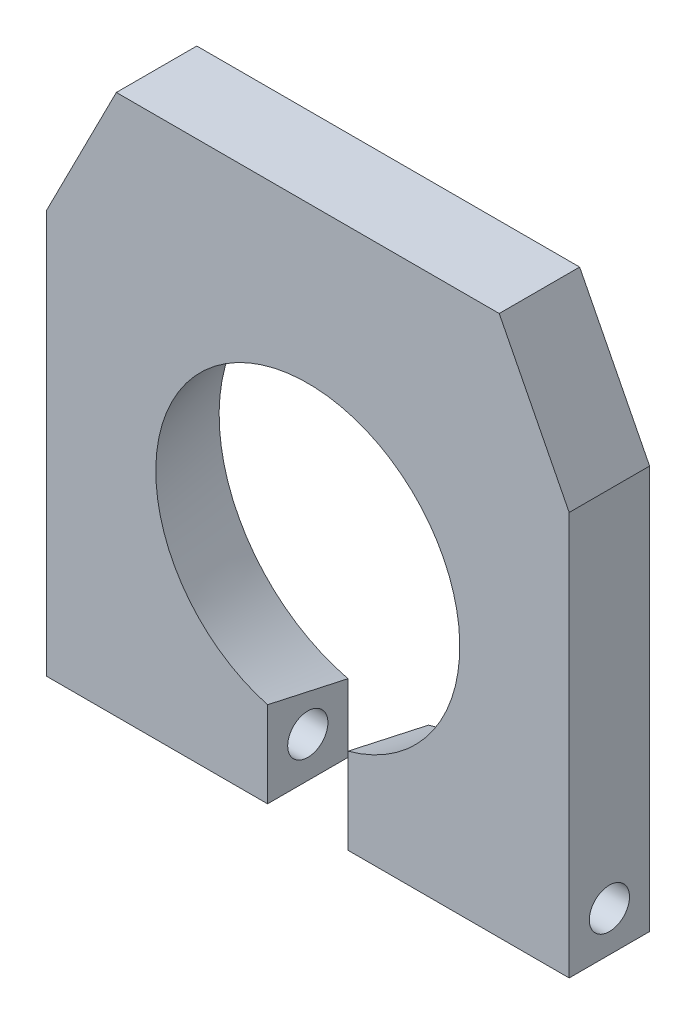
SolidWorks part; units mm, degrees
material "Alliage 1060"
ref_plane "Plan de face" through (0, 0, 0) normal (0, 0, 1) x (1, 0, 0)
ref_plane "Plan de dessus" through (0, 0, 0) normal (0, 1, 0) x (1, 0, 0)
ref_plane "Plan de droite" through (0, 0, 0) normal (1, 0, 0) x (0, 0, -1)
sketch "Esquisse1" plane through (0, 0, 0) normal (0, 0, 1) x (1, 0, 0)
  line L0 (34.925, -85.344) -> (34.925, -71.7887)
  line L1 (0, 0) -> (82.55, 0)
  line L2 (0, 0) -> (0, -85.344)
  line L3 (0, -85.344) -> (34.925, -85.344)
  line L4 (82.55, 0) -> (82.55, -85.344)
  line L5 (47.625, -85.344) -> (82.55, -85.344)
  line L6 (47.625, -71.7887) -> (47.625, -85.344)
  line L7 (34.925, -85.344) -> (47.625, -85.344) construction
  arc A0 (47.625, -71.7887) -> (34.925, -71.7887) centre (41.275, -48.644) ccw
  point P6 (41.275, -85.344)
  point P7 (41.275, 0)
  dimension "D3" = 48
  dimension "D1" = 82.55
  dimension "D2" = 85.344
  dimension "D4" = 12.7
  dimension "D5" = 12.7
extrude "Boss.-Extru.1" add sketch "Esquisse1" along normal blind 12.7
ref_axis "Axe1" through (41.275, -48.644, 0) along (0, 0, 1)
sketch "Esquisse2" plane through (82.55, 0, 0) normal (1, 0, 0) x (0, 0, -1)
  line L0 (-6.35, -78.994) -> (-12.7, -85.344) construction
  line L1 (-6.35, -78.994) -> (0, -85.344) construction
  line L2 (-6.35, -78.994) -> (-12.7, -78.994) construction
  line L3 (-12.7, -85.344) -> (-12.7, 0) construction
  line L4 (-6.35, -78.994) -> (-6.35, -85.344) construction
  line L5 (-12.7, -85.344) -> (0, -85.344) construction
  circle A0 centre (-6.35, -78.994) radius 3.175
  dimension "D1" = 6.35
extrude "Enlèv. mat.-Extru.1" cut sketch "Esquisse2" against normal through all
ref_plane "Plan1" through (0, -48.644, 0) normal (0, -1, 0) x (1, 0, 0)
sketch "Esquisse4" plane through (0, -48.644, 0) normal (0, -1, 0) x (1, 0, 0)
  line L0 (17.275, 12.7) -> (14.5338, -0.1963)
  line L1 (17.275, 12.7) -> (34.925, 12.7)
  line L2 (14.5338, -0.1963) -> (34.925, -0.1963)
  line L6 (34.925, -0.1963) -> (34.925, 12.7)
  dimension "D1" = 102
  dimension "D2" = 12.8963
revolve "Enlèvement de matière-Révolution1" cut sketch "Esquisse4" angle 360 about axis through (41.275, -48.644, 0) along (0, 0, 1)
sketch "Esquisse5" plane through (0, 0, 0) normal (0, 0, -1) x (-1, 0, 0)
  line L0 (-71.501, 0) -> (-11.049, 0) construction
  line L1 (0, 0) -> (-82.55, 0) construction
  line L2 (-71.501, 0) -> (-82.55, -21.6849)
  line L3 (-82.55, 0) -> (-82.55, -85.344) construction
  line L4 (-82.55, -21.6849) -> (-82.55, 0)
  line L5 (-82.55, 0) -> (-71.501, 0)
  line L6 (-11.049, 0) -> (0, -21.6849)
  line L7 (0, 0) -> (0, -85.344) construction
  line L8 (0, -21.6849) -> (0, 0)
  line L9 (0, 0) -> (-11.049, 0)
  point P4 (-41.275, 0)
  point P7 (-41.275, 0)
  dimension "D1" = 60.452
  dimension "D2" = 27
extrude "Enlèv. mat.-Extru.2" cut sketch "Esquisse5" against normal through all
